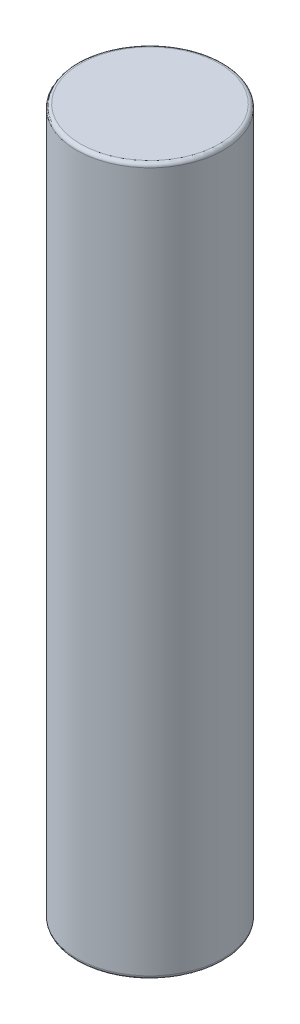
SolidWorks part; units mm, degrees
material "Plain Carbon Steel"
ref_plane "Front Plane" through (0, 0, 0) normal (0, 0, 1) x (1, 0, 0)
ref_plane "Top Plane" through (0, 0, 0) normal (0, 1, 0) x (1, 0, 0)
ref_plane "Right Plane" through (0, 0, 0) normal (1, 0, 0) x (0, 0, -1)
sketch "Sketch1" plane through (0, 0, 0) normal (0, 1, 0) x (1, 0, 0)
  circle A0 centre (0, 0) radius 2.5
  dimension "D1" = 5
extrude "Boss-Extrude1" add sketch "Sketch1" along normal blind 24.13
fillet "Fillet1" radius 0.127 2 edges at (0, 0, 2.5) (0, 24.13, 2.5)
